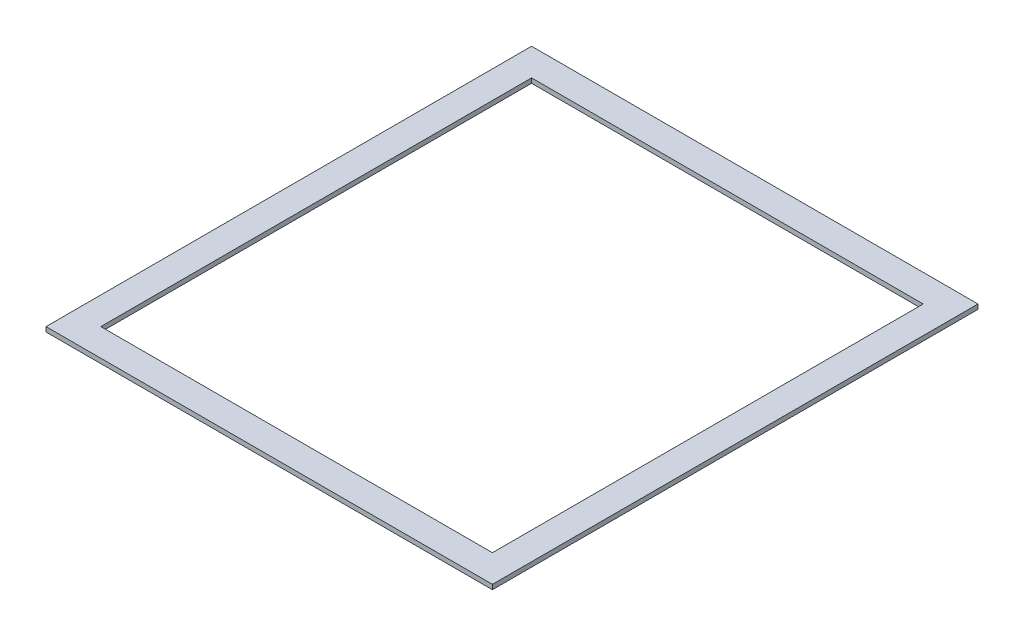
SolidWorks part; units mm, degrees
ref_plane "Front Plane" through (0, 0, 0) normal (0, 0, 1) x (1, 0, 0)
ref_plane "Top Plane" through (0, 0, 0) normal (0, 1, 0) x (1, 0, 0)
ref_plane "Right Plane" through (0, 0, 0) normal (1, 0, 0) x (0, 0, -1)
sketch "Sketch1" plane through (0, 0, 0) normal (0, 1, 0) x (1, 0, 0)
  line L1 (-28.5, 31) -> (28.5, 31)
  line L2 (-28.5, 31) -> (-28.5, -31)
  line L3 (-28.5, -31) -> (28.5, -31)
  line L4 (28.5, 31) -> (28.5, -31)
  line L5 (-28.5, 31) -> (28.5, -31) construction
  line L6 (-28.5, -31) -> (28.5, 31) construction
  line L7 (-25, -27.5) -> (25, -27.5)
  line L8 (-25, -27.5) -> (-25, 27.5)
  line L9 (-25, 27.5) -> (25, 27.5)
  line L10 (25, -27.5) -> (25, 27.5)
  line L11 (-25, -27.5) -> (25, 27.5) construction
  line L12 (-25, 27.5) -> (25, -27.5) construction
  point P0 (0, 0)
  point P6 (0, 0)
  dimension "D1" = 62
  dimension "D2" = 57
  dimension "D3" = 50
  dimension "D4" = 55
extrude "Boss-Extrude1" add sketch "Sketch1" along normal blind 0.6
